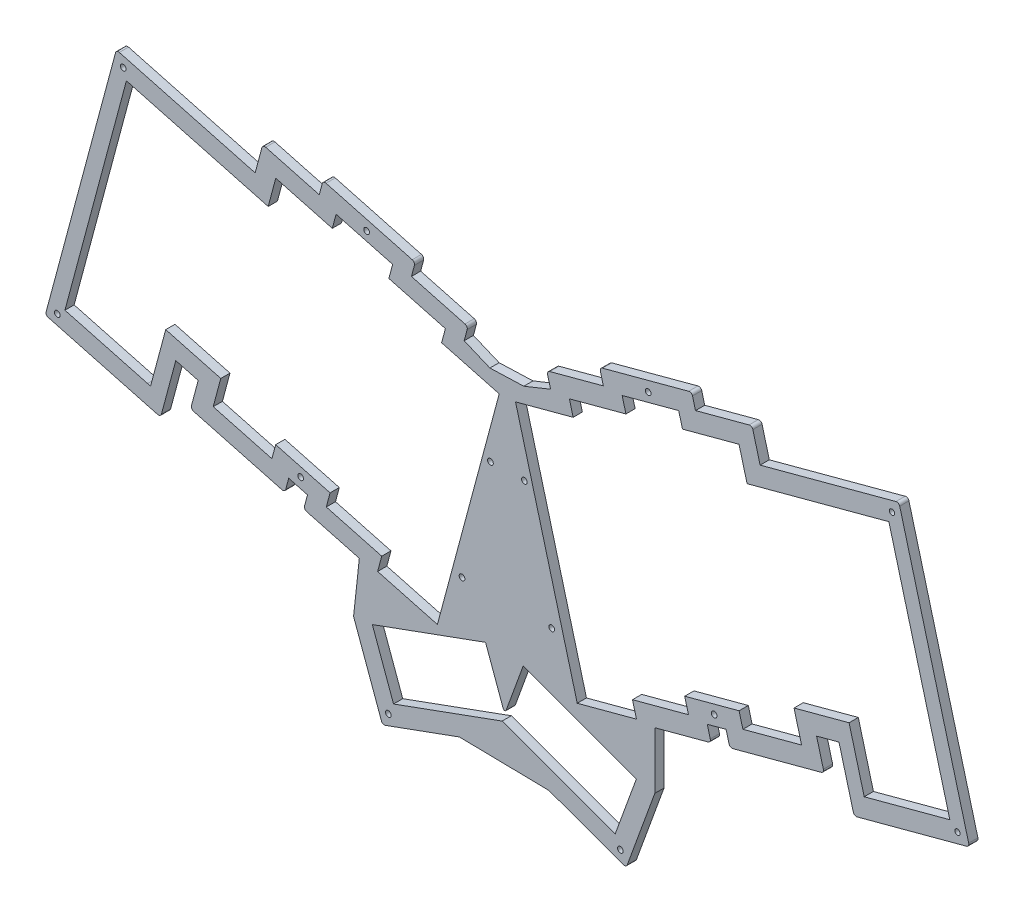
SolidWorks part; units mm, degrees
ref_plane "Front Plane" through (0, 0, 0) normal (0, 0, 1) x (1, 0, 0)
ref_plane "Top Plane" through (0, 0, 0) normal (0, 1, 0) x (1, 0, 0)
ref_plane "Right Plane" through (0, 0, 0) normal (1, 0, 0) x (0, 0, -1)
sketch "Model" plane through (0, 0, 0) normal (0, 0, 1) x (1, 0, 0)
  line L0 (282.165, 226.202) -> (288.4436, 227.8841) construction
  line L1 (267.373, 281.405) -> (273.6516, 283.0871) construction
  line L2 (195.392, 284.0785) -> (194.5766, 287.1211) construction
  line L3 (100.681, 283.685) -> (101.4961, 286.7277) construction
  line L4 (168.22, 168.742) -> (181.234, 164.006) construction
  line L5 (181.234, 164.006) -> (185.972, 177.021) construction
  line L6 (185.972, 177.021) -> (172.956, 181.758) construction
  line L7 (172.956, 181.758) -> (168.22, 168.742) construction
  line L8 (132.176, 184.752) -> (133.281, 181.717) construction
  line L9 (133.281, 181.717) -> (131.706, 181.144) construction
  line L10 (131.706, 181.144) -> (130.099, 185.56) construction
  line L11 (130.099, 185.56) -> (117.085, 180.823) construction
  line L12 (117.085, 180.823) -> (118.692, 176.407) construction
  line L13 (118.692, 176.407) -> (117.118, 175.834) construction
  line L14 (117.118, 175.834) -> (116.013, 178.869) construction
  line L15 (116.013, 178.869) -> (109.812, 176.612) construction
  line L16 (109.812, 176.612) -> (110.917, 173.576) construction
  line L17 (110.917, 173.576) -> (110.141, 173.294) construction
  line L18 (110.141, 173.294) -> (111.048, 170.804) construction
  line L19 (111.048, 170.804) -> (111.822, 171.086) construction
  line L20 (111.822, 171.086) -> (113.968, 165.194) construction
  line L21 (113.968, 165.194) -> (115.588, 165.784) construction
  line L22 (115.588, 165.784) -> (115.999, 164.656) construction
  line L23 (115.999, 164.656) -> (118.959, 165.734) construction
  line L24 (118.959, 165.734) -> (118.549, 166.861) construction
  line L25 (118.549, 166.861) -> (120.169, 167.452) construction
  line L26 (120.169, 167.452) -> (118.641, 171.651) construction
  line L27 (118.641, 171.651) -> (120.215, 172.224) construction
  line L28 (120.215, 172.224) -> (121.821, 167.809) construction
  line L29 (121.821, 167.809) -> (134.837, 172.545) construction
  line L30 (134.837, 172.545) -> (133.23, 176.962) construction
  line L31 (133.23, 176.962) -> (134.804, 177.535) construction
  line L32 (134.804, 177.535) -> (136.332, 173.335) construction
  line L33 (136.332, 173.335) -> (137.953, 173.925) construction
  line L34 (137.953, 173.925) -> (138.363, 172.796) construction
  line L35 (138.363, 172.796) -> (141.323, 173.874) construction
  line L36 (141.323, 173.874) -> (140.913, 175.001) construction
  line L37 (140.913, 175.001) -> (142.533, 175.592) construction
  line L38 (142.533, 175.592) -> (140.389, 181.483) construction
  line L39 (140.389, 181.483) -> (141.165, 181.766) construction
  line L40 (141.165, 181.766) -> (140.258, 184.256) construction
  line L41 (140.258, 184.256) -> (139.484, 183.974) construction
  line L42 (139.484, 183.974) -> (138.378, 187.009) construction
  line L43 (138.378, 187.009) -> (132.176, 184.752) construction
  line L44 (150.319, 175.258) -> (163.333, 170.521) construction
  line L45 (163.333, 170.521) -> (168.071, 183.535) construction
  line L46 (168.071, 183.535) -> (155.055, 188.273) construction
  line L47 (155.055, 188.273) -> (150.319, 175.258) construction
  line L48 (109.952, 197.835) -> (123.33, 194.251) construction
  line L49 (123.33, 194.251) -> (126.916, 207.629) construction
  line L50 (126.916, 207.629) -> (113.537, 211.213) construction
  line L51 (113.537, 211.213) -> (109.952, 197.835) construction
  line L52 (169.157, 208.022) -> (172.741, 194.644) construction
  line L53 (172.741, 194.644) -> (186.119, 198.228) construction
  line L54 (186.119, 198.228) -> (182.535, 211.607) construction
  line L55 (182.535, 211.607) -> (169.157, 208.022) construction
  line L56 (92.7848, 207.366) -> (106.163, 203.781) construction
  line L57 (106.163, 203.781) -> (109.747, 217.159) construction
  line L58 (109.747, 217.159) -> (96.369, 220.744) construction
  line L59 (96.369, 220.744) -> (92.7848, 207.366) construction
  line L60 (186.326, 217.552) -> (189.91, 204.174) construction
  line L61 (189.91, 204.174) -> (203.288, 207.759) construction
  line L62 (203.288, 207.759) -> (199.704, 221.137) construction
  line L63 (199.704, 221.137) -> (186.326, 217.552) construction
  line L64 (114.883, 216.236) -> (128.261, 212.652) construction
  line L65 (128.261, 212.652) -> (131.845, 226.03) construction
  line L66 (131.845, 226.03) -> (118.467, 229.614) construction
  line L67 (118.467, 229.614) -> (114.883, 216.236) construction
  line L68 (164.226, 226.423) -> (167.812, 213.045) construction
  line L69 (167.812, 213.045) -> (181.19, 216.629) construction
  line L70 (181.19, 216.629) -> (177.604, 230.007) construction
  line L71 (177.604, 230.007) -> (164.226, 226.423) construction
  line L72 (75.6158, 216.896) -> (88.9938, 213.312) construction
  line L73 (88.9938, 213.312) -> (92.5781, 226.69) construction
  line L74 (92.5781, 226.69) -> (79.2, 230.274) construction
  line L75 (79.2, 230.274) -> (75.6158, 216.896) construction
  line L76 (55.9827, 217.227) -> (69.3607, 213.643) construction
  line L77 (69.3607, 213.643) -> (72.9449, 227.021) construction
  line L78 (72.9449, 227.021) -> (59.5672, 230.605) construction
  line L79 (59.5672, 230.605) -> (55.9827, 217.227) construction
  line L80 (203.494, 227.083) -> (207.078, 213.705) construction
  line L81 (207.078, 213.705) -> (220.457, 217.29) construction
  line L82 (220.457, 217.29) -> (216.872, 230.668) construction
  line L83 (216.872, 230.668) -> (203.494, 227.083) construction
  line L84 (223.128, 227.414) -> (226.712, 214.036) construction
  line L85 (226.712, 214.036) -> (240.09, 217.62) construction
  line L86 (240.09, 217.62) -> (236.506, 230.998) construction
  line L87 (236.506, 230.998) -> (223.128, 227.414) construction
  line L88 (12.1157, 219.121) -> (25.4937, 215.536) construction
  line L89 (25.4937, 215.536) -> (29.078, 228.914) construction
  line L90 (29.078, 228.914) -> (15.7, 232.499) construction
  line L91 (15.7, 232.499) -> (12.1157, 219.121) construction
  line L92 (266.995, 229.307) -> (270.579, 215.929) construction
  line L93 (270.579, 215.929) -> (283.957, 219.513) construction
  line L94 (283.957, 219.513) -> (280.373, 232.891) construction
  line L95 (280.373, 232.891) -> (266.995, 229.307) construction
  line L96 (97.7138, 225.767) -> (111.092, 222.183) construction
  line L97 (111.092, 222.183) -> (114.677, 235.56) construction
  line L98 (114.677, 235.56) -> (101.299, 239.145) construction
  line L99 (101.299, 239.145) -> (97.7138, 225.767) construction
  line L100 (181.394, 235.953) -> (184.98, 222.575) construction
  line L101 (184.98, 222.575) -> (198.357, 226.159) construction
  line L102 (198.357, 226.159) -> (194.773, 239.538) construction
  line L103 (194.773, 239.538) -> (181.394, 235.953) construction
  line L104 (40.0473, 231.357) -> (53.425, 227.773) construction
  line L105 (53.425, 227.773) -> (57.0096, 241.151) construction
  line L106 (57.0096, 241.151) -> (43.6316, 244.735) construction
  line L107 (43.6316, 244.735) -> (40.0473, 231.357) construction
  line L108 (239.062, 241.545) -> (242.648, 228.166) construction
  line L109 (242.648, 228.166) -> (256.024, 231.75) construction
  line L110 (256.024, 231.75) -> (252.44, 245.128) construction
  line L111 (252.44, 245.128) -> (239.062, 241.545) construction
  line L112 (119.814, 234.637) -> (133.192, 231.053) construction
  line L113 (133.192, 231.053) -> (136.776, 244.431) construction
  line L114 (136.776, 244.431) -> (123.396, 248.015) construction
  line L115 (123.396, 248.015) -> (119.814, 234.637) construction
  line L116 (159.297, 244.824) -> (162.88, 231.445) construction
  line L117 (162.88, 231.445) -> (176.258, 235.03) construction
  line L118 (176.258, 235.03) -> (172.675, 248.408) construction
  line L119 (172.675, 248.408) -> (159.297, 244.824) construction
  line L120 (80.5462, 235.297) -> (93.9243, 231.713) construction
  line L121 (93.9243, 231.713) -> (97.5099, 245.091) construction
  line L122 (97.5099, 245.091) -> (84.1304, 248.675) construction
  line L123 (84.1304, 248.675) -> (80.5462, 235.297) construction
  line L124 (60.912, 235.628) -> (74.2901, 232.044) construction
  line L125 (74.2901, 232.044) -> (77.8757, 245.422) construction
  line L126 (77.8757, 245.422) -> (64.4977, 249.006) construction
  line L127 (64.4977, 249.006) -> (60.912, 235.628) construction
  line L128 (198.563, 245.484) -> (202.147, 232.106) construction
  line L129 (202.147, 232.106) -> (215.525, 235.692) construction
  line L130 (215.525, 235.692) -> (211.941, 249.069) construction
  line L131 (211.941, 249.069) -> (198.563, 245.484) construction
  line L132 (218.196, 245.814) -> (221.782, 232.436) construction
  line L133 (221.782, 232.436) -> (235.16, 236.021) construction
  line L134 (235.16, 236.021) -> (231.574, 249.399) construction
  line L135 (231.574, 249.399) -> (218.196, 245.814) construction
  line L136 (17.045, 237.521) -> (30.423, 233.937) construction
  line L137 (30.423, 233.937) -> (34.0086, 247.315) construction
  line L138 (34.0086, 247.315) -> (20.6306, 250.899) construction
  line L139 (20.6306, 250.899) -> (17.045, 237.521) construction
  line L140 (262.063, 247.708) -> (265.649, 234.33) construction
  line L141 (265.649, 234.33) -> (279.026, 237.914) construction
  line L142 (279.026, 237.914) -> (275.442, 251.292) construction
  line L143 (275.442, 251.292) -> (262.063, 247.708) construction
  line L144 (102.646, 244.168) -> (116.024, 240.584) construction
  line L145 (116.024, 240.584) -> (119.607, 253.962) construction
  line L146 (119.607, 253.962) -> (106.229, 257.546) construction
  line L147 (106.229, 257.546) -> (102.646, 244.168) construction
  line L148 (176.465, 254.354) -> (180.049, 240.976) construction
  line L149 (180.049, 240.976) -> (193.427, 244.56) construction
  line L150 (193.427, 244.56) -> (189.843, 257.938) construction
  line L151 (189.843, 257.938) -> (176.465, 254.354) construction
  line L152 (44.9778, 249.759) -> (58.3558, 246.174) construction
  line L153 (58.3558, 246.174) -> (61.94, 259.553) construction
  line L154 (61.94, 259.553) -> (48.562, 263.136) construction
  line L155 (48.562, 263.136) -> (44.9778, 249.759) construction
  line L156 (234.133, 259.945) -> (237.717, 246.567) construction
  line L157 (237.717, 246.567) -> (251.095, 250.151) construction
  line L158 (251.095, 250.151) -> (247.511, 263.529) construction
  line L159 (247.511, 263.529) -> (234.133, 259.945) construction
  line L160 (124.743, 253.038) -> (138.122, 249.454) construction
  line L161 (138.122, 249.454) -> (141.707, 262.832) construction
  line L162 (141.707, 262.832) -> (128.329, 266.416) construction
  line L163 (128.329, 266.416) -> (124.743, 253.038) construction
  line L164 (154.365, 263.224) -> (157.951, 249.845) construction
  line L165 (157.951, 249.845) -> (171.329, 253.432) construction
  line L166 (171.329, 253.432) -> (167.743, 266.809) construction
  line L167 (167.743, 266.809) -> (154.365, 263.224) construction
  line L168 (85.477, 253.699) -> (98.855, 250.114) construction
  line L169 (98.855, 250.114) -> (102.439, 263.492) construction
  line L170 (102.439, 263.492) -> (89.0612, 267.076) construction
  line L171 (89.0612, 267.076) -> (85.477, 253.699) construction
  line L172 (65.8442, 254.03) -> (79.2219, 250.443) construction
  line L173 (79.2219, 250.443) -> (82.8065, 263.823) construction
  line L174 (82.8065, 263.823) -> (69.427, 267.407) construction
  line L175 (69.427, 267.407) -> (65.8442, 254.03) construction
  line L176 (193.632, 263.885) -> (197.218, 250.507) construction
  line L177 (197.218, 250.507) -> (210.596, 254.092) construction
  line L178 (210.596, 254.092) -> (207.01, 267.47) construction
  line L179 (207.01, 267.47) -> (193.632, 263.885) construction
  line L180 (213.267, 264.215) -> (216.851, 250.837) construction
  line L181 (216.851, 250.837) -> (230.229, 254.422) construction
  line L182 (230.229, 254.422) -> (226.645, 267.8) construction
  line L183 (226.645, 267.8) -> (213.267, 264.215) construction
  line L184 (21.977, 255.922) -> (35.355, 252.338) construction
  line L185 (35.355, 252.338) -> (38.9378, 265.716) construction
  line L186 (38.9378, 265.716) -> (25.5598, 269.3) construction
  line L187 (25.5598, 269.3) -> (21.977, 255.922) construction
  line L188 (257.132, 266.109) -> (260.718, 252.729) construction
  line L189 (260.718, 252.729) -> (274.096, 256.315) construction
  line L190 (274.096, 256.315) -> (270.512, 269.693) construction
  line L191 (270.512, 269.693) -> (257.132, 266.109) construction
  line L192 (107.575, 262.569) -> (120.953, 258.984) construction
  line L193 (120.953, 258.984) -> (124.539, 272.362) construction
  line L194 (124.539, 272.362) -> (111.161, 275.947) construction
  line L195 (111.161, 275.947) -> (107.575, 262.569) construction
  line L196 (171.534, 272.755) -> (175.118, 259.377) construction
  line L197 (175.118, 259.377) -> (188.496, 262.961) construction
  line L198 (188.496, 262.961) -> (184.912, 276.339) construction
  line L199 (184.912, 276.339) -> (171.534, 272.755) construction
  line L200 (49.9071, 268.159) -> (63.2852, 264.575) construction
  line L201 (63.2852, 264.575) -> (66.8708, 277.953) construction
  line L202 (66.8708, 277.953) -> (53.4928, 281.537) construction
  line L203 (53.4928, 281.537) -> (49.9071, 268.159) construction
  line L204 (229.201, 278.346) -> (232.786, 264.968) construction
  line L205 (232.786, 264.968) -> (246.164, 268.554) construction
  line L206 (246.164, 268.554) -> (242.579, 281.932) construction
  line L207 (242.579, 281.932) -> (229.201, 278.346) construction
  line L208 (90.4074, 272.099) -> (103.785, 268.515) construction
  line L209 (103.785, 268.515) -> (107.37, 281.893) construction
  line L210 (107.37, 281.893) -> (93.992, 285.477) construction
  line L211 (93.992, 285.477) -> (90.4074, 272.099) construction
  line L212 (70.7732, 272.43) -> (84.1513, 268.844) construction
  line L213 (84.1513, 268.844) -> (87.7369, 282.222) construction
  line L214 (87.7369, 282.222) -> (74.3589, 285.808) construction
  line L215 (74.3589, 285.808) -> (70.7732, 272.43) construction
  line L216 (188.703, 282.286) -> (192.286, 268.908) construction
  line L217 (192.286, 268.908) -> (205.664, 272.493) construction
  line L218 (205.664, 272.493) -> (202.081, 285.871) construction
  line L219 (202.081, 285.871) -> (188.703, 282.286) construction
  line L220 (208.336, 282.616) -> (211.92, 269.238) construction
  line L221 (211.92, 269.238) -> (225.298, 272.822) construction
  line L222 (225.298, 272.822) -> (221.714, 286.2) construction
  line L223 (221.714, 286.2) -> (208.336, 282.616) construction
  line L224 (26.9062, 274.323) -> (40.284, 270.739) construction
  line L225 (40.284, 270.739) -> (43.8697, 284.117) construction
  line L226 (43.8697, 284.117) -> (30.4919, 287.701) construction
  line L227 (30.4919, 287.701) -> (26.9062, 274.323) construction
  line L228 (252.203, 284.508) -> (255.786, 271.131) construction
  line L229 (255.786, 271.131) -> (269.165, 274.716) construction
  line L230 (269.165, 274.716) -> (265.581, 288.094) construction
  line L231 (265.581, 288.094) -> (252.203, 284.508) construction
  line L232 (37.1808, 285.909) -> (37.996, 288.9517) construction
  line L233 (28.6991, 281.012) -> (22.4207, 282.6948) construction
  line L234 (18.8047, 217.3285) -> (17.9893, 214.2859) construction
  line L235 (13.9078, 225.81) -> (7.6293, 227.4922) construction
  line L236 (277.268, 217.721) -> (278.0831, 214.6783) construction
  line L237 (271.2035, 292.2232) -> (291.0512, 218.1525) construction
  line L238 (241.3027, 224.5444) -> (243.7675, 215.3441)
  line L239 (81.0479, 284.015) -> (81.8635, 287.0576) construction
  line L240 (181.234, 164.006) -> (184.194, 162.9285) construction
  line L241 (91.0631, 284.5916) -> (72.6639, 289.5236)
  line L242 (117.85, 274.1545) -> (118.6654, 277.1971) construction
  line L243 (135.018, 264.624) -> (135.8331, 267.6667) construction
  line L244 (161.054, 265.0165) -> (160.2386, 268.0591) construction
  line L245 (178.223, 274.547) -> (177.4079, 277.5897) construction
  line L246 (215.025, 284.408) -> (214.2099, 287.4507) construction
  line L247 (258.892, 286.301) -> (258.2357, 288.7493) construction
  line L248 (196.599, 205.9665) -> (197.4144, 202.9239) construction
  line L249 (92.2965, 289.1937) -> (110.6958, 284.2617)
  line L250 (213.7675, 215.4975) -> (214.5828, 212.4548) construction
  line L251 (233.401, 215.828) -> (234.2161, 212.7853) construction
  line L252 (62.6717, 215.435) -> (61.8566, 212.3923) construction
  line L253 (82.3048, 215.104) -> (81.4897, 212.0613) construction
  line L254 (99.4739, 205.5735) -> (98.6586, 202.5309) construction
  line L255 (35.8867, 229.2106) -> (54.7701, 224.1516) construction
  line L256 (60.1818, 279.745) -> (60.9969, 282.7877) construction
  line L257 (72.6639, 289.5236) -> (70.1982, 280.3232)
  line L258 (105.8147, 195.273) -> (104.0964, 179.4507) construction
  line L259 (52.3052, 214.9511) -> (54.7701, 224.1516)
  line L260 (260.1862, 229.6041) -> (265.1156, 211.2042) construction
  line L261 (203.777, 289.5866) -> (185.3762, 284.6556)
  line L262 (30.9571, 210.8115) -> (35.8867, 229.2106) construction
  line L263 (141.707, 262.832) -> (142.5224, 265.8746) construction
  line L264 (154.365, 263.224) -> (153.5495, 266.2666) construction
  line L265 (181.234, 164.006) -> (180.1565, 161.046) construction
  line L266 (92.2965, 289.1937) -> (91.0631, 284.5916)
  line L267 (169.4396, 270.5248) -> (150.6904, 265.5004)
  line L268 (110.6958, 284.2617) -> (109.4634, 279.6637)
  line L269 (127.8626, 274.7318) -> (126.6303, 270.1341)
  line L270 (127.8626, 274.7318) -> (109.4634, 279.6637)
  line L271 (260.1862, 229.6041) -> (241.3027, 224.5444) construction
  line L272 (126.6303, 270.1341) -> (145.3813, 265.1084)
  line L273 (185.3762, 284.6556) -> (186.6084, 280.0546)
  line L274 (142.3447, 270.8715) -> (153.3719, 271.2634)
  line L275 (203.777, 289.5866) -> (205.0099, 284.986)
  line L276 (168.2073, 275.1248) -> (169.4396, 270.5248)
  line L277 (205.0099, 284.986) -> (223.4098, 289.9154)
  line L278 (223.4098, 289.9154) -> (226.0333, 280.1226)
  line L279 (186.6084, 280.0546) -> (168.2073, 275.1248)
  line L280 (104.0964, 179.4507) -> (110.9864, 160.5147)
  line L281 (152.687, 181.7655) -> (183.603, 170.5135) construction
  line L282 (110.5015, 171.0598) -> (141.4185, 182.3092) construction
  line L283 (27.2858, 222.225) -> (33.5644, 220.5428) construction
  line L284 (90.3394, 209.6904) -> (72.6399, 214.4322)
  line L285 (71.4079, 209.8335) -> (72.6399, 214.4322)
  line L286 (89.1069, 205.0898) -> (90.3394, 209.6904)
  line L287 (89.1069, 205.0898) -> (107.1497, 200.256)
  line L288 (107.1497, 200.256) -> (105.8147, 195.273)
  line L289 (110.9864, 160.5147) -> (131.4289, 167.9529)
  line L290 (71.4079, 209.8335) -> (52.3052, 214.9511)
  line L291 (5.0216, 217.7602) -> (25.0282, 292.4264) construction
  line L292 (130.099, 185.56) -> (121.821, 167.809) construction
  line L293 (190.0384, 195.7708) -> (190.0096, 178.9037) construction
  line L294 (235.89, 280.139) -> (235.2337, 282.5873) construction
  line L295 (162.6744, 167.408) -> (183.1165, 159.9688)
  line L296 (131.4289, 167.9529) -> (162.6744, 167.408) construction
  line L297 (5.0216, 217.7602) -> (30.9571, 210.8115)
  line L298 (46.7361, 229.565) -> (45.921, 226.5223) construction
  line L299 (265.1156, 211.2042) -> (291.0512, 218.1525)
  line L300 (25.0282, 292.4264) -> (70.1982, 280.3232)
  line L301 (226.0333, 280.1226) -> (271.2035, 292.2232)
  line L302 (216.1359, 206.6593) -> (215.3122, 209.7329) construction
  line L303 (128.329, 170.177) -> (129.4061, 167.2169) construction
  line L304 (249.336, 229.958) -> (250.1513, 226.9153) construction
  line L305 (268.787, 222.618) -> (262.5084, 220.9359) construction
  line L306 (109.952, 197.835) -> (106.7322, 198.6976) construction
  line L307 (-2.3268, 213.5174) -> (20.7855, 299.7748)
  line L308 (186.119, 198.228) -> (189.1617, 199.0431) construction
  line L309 (206.9661, 205.4835) -> (188.7445, 200.6005)
  line L310 (188.7445, 200.6005) -> (190.0384, 195.7708)
  line L311 (20.7855, 299.7748) -> (65.9558, 287.6716)
  line L312 (68.4216, 296.8725) -> (65.9558, 287.6716)
  line L313 (86.821, 291.9405) -> (68.4216, 296.8725)
  line L314 (88.0544, 296.5426) -> (86.821, 291.9405)
  line L315 (88.0544, 296.5426) -> (118.0445, 288.5037)
  line L316 (118.0445, 288.5037) -> (116.8121, 283.9057)
  line L317 (135.2113, 278.9738) -> (116.8121, 283.9057)
  line L318 (135.2113, 278.9738) -> (133.9791, 274.3762)
  line L319 (133.9791, 274.3762) -> (142.3447, 270.8715)
  line L320 (153.3719, 271.2634) -> (162.0915, 274.7674)
  line L321 (20.7855, 299.7748) -> (25.0282, 292.4264) construction
  line L322 (160.859, 279.3678) -> (162.0915, 274.7674)
  line L323 (179.2607, 284.2977) -> (160.859, 279.3678)
  line L324 (178.0286, 288.8984) -> (179.2607, 284.2977)
  line L325 (208.0195, 296.9352) -> (178.0286, 288.8984)
  line L326 (208.0195, 296.9352) -> (209.2525, 292.3342)
  line L327 (209.2525, 292.3342) -> (227.6528, 297.2637)
  line L328 (227.6528, 297.2637) -> (230.2763, 287.4708)
  line L329 (230.2763, 287.4708) -> (275.4462, 299.5713)
  line L330 (298.3998, 213.9096) -> (294.5027, 216.1597) construction
  line L331 (275.4462, 299.5713) -> (298.3998, 213.9096)
  line L332 (260.8726, 203.856) -> (298.3998, 213.9096)
  line L333 (255.9433, 222.2556) -> (260.8726, 203.856)
  line L334 (255.9433, 222.2556) -> (248.6509, 220.3017)
  line L335 (183.1165, 159.9688) -> (190.0096, 178.9037)
  line L336 (248.6509, 220.3017) -> (251.1158, 211.1012)
  line L337 (220.4222, 202.8783) -> (251.1158, 211.1012)
  line L338 (219.1898, 207.4775) -> (220.4222, 202.8783)
  line L339 (213.082, 205.8412) -> (219.1898, 207.4775)
  line L340 (206.9661, 205.4835) -> (205.7333, 210.084)
  line L341 (223.4323, 214.8256) -> (224.6648, 210.2265)
  line L342 (205.7333, 210.084) -> (223.4323, 214.8256)
  line L343 (214.3147, 201.2411) -> (213.082, 205.8412)
  line L344 (214.3147, 201.2411) -> (196.0393, 196.3437)
  line L345 (224.6648, 210.2265) -> (243.7675, 215.3441)
  line L346 (196.0393, 196.3437) -> (196.0078, 177.8406)
  line L347 (150.6904, 265.5004) -> (170.7656, 190.6076)
  line L348 (186.7023, 152.2789) -> (196.0078, 177.8406)
  line L349 (161.566, 161.4264) -> (186.7023, 152.2789)
  line L350 (132.4358, 161.9344) -> (161.566, 161.4264)
  line L351 (107.3996, 152.8248) -> (132.4358, 161.9344)
  line L352 (97.9807, 178.7109) -> (107.3996, 152.8248)
  line L353 (99.8582, 195.9979) -> (97.9807, 178.7109)
  line L354 (141.707, 262.832) -> (154.365, 263.224) construction
  line L355 (81.7586, 200.8468) -> (99.8582, 195.9979)
  line L356 (81.7586, 200.8468) -> (82.9911, 205.4475)
  line L357 (82.9911, 205.4475) -> (76.8829, 207.0839)
  line L358 (75.6509, 202.4852) -> (76.8829, 207.0839)
  line L359 (75.6509, 202.4852) -> (44.9569, 210.7082)
  line L360 (44.9569, 210.7082) -> (47.4218, 219.9086)
  line L361 (40.1295, 221.8623) -> (47.4218, 219.9086)
  line L362 (35.1999, 203.4631) -> (40.1295, 221.8623)
  line L363 (-2.3268, 213.5174) -> (35.1999, 203.4631)
  line L364 (20.7855, 299.7748) -> (23.0356, 295.8777) construction
  line L365 (142.5224, 265.8746) -> (153.5495, 266.2666) construction
  line L366 (275.4462, 299.5713) -> (271.2035, 292.2232) construction
  line L367 (291.0512, 218.1525) -> (298.3998, 213.9096) construction
  line L368 (-2.3268, 213.5174) -> (5.0216, 217.7602) construction
  line L369 (107.3996, 152.8248) -> (110.9864, 160.5147) construction
  line L370 (183.1165, 159.9688) -> (186.7023, 152.2789) construction
  line L371 (107.3996, 152.8248) -> (109.3018, 156.903) construction
  line L372 (184.8006, 156.3573) -> (186.7023, 152.2789) construction
  line L373 (106.163, 203.781) -> (189.91, 204.174) construction
  line L374 (101.4961, 286.7277) -> (103.0495, 292.5232) construction
  line L375 (194.5766, 287.1211) -> (193.0241, 292.9168) construction
  line L376 (23.0356, 295.8777) -> (23.8591, 298.9513) construction
  line L377 (193.0241, 292.9168) -> (193.8474, 289.8432) construction
  line L378 (214.5828, 212.4548) -> (216.1359, 206.6593) construction
  line L379 (103.0495, 292.5232) -> (102.2257, 289.4497) construction
  line L380 (275.4462, 299.5713) -> (273.1961, 295.6743) construction
  line L381 (-2.3268, 213.5174) -> (1.5702, 215.7675) construction
  line L382 (81.4897, 212.0613) -> (79.937, 206.2657) construction
  line L383 (81.4897, 212.0613) -> (79.937, 206.2657) construction
  line L384 (214.5828, 212.4548) -> (216.1359, 206.6593) construction
  line L385 (145.3813, 265.1084) -> (125.265, 190.0622)
  line L386 (190.0384, 195.7708) -> (170.7656, 190.6076)
  line L387 (148.0359, 266.0706) -> (148.0365, 203.9775) construction
  line L388 (105.8147, 195.273) -> (125.265, 190.0622)
  line L389 (104.0964, 179.4507) -> (140.9309, 192.8582)
  line L390 (190.0096, 178.9037) -> (153.1726, 192.3111)
  line L391 (152.687, 181.7655) -> (149.727, 182.8428) construction
  line L392 (131.4289, 167.9529) -> (146.3042, 173.3654)
  line L393 (153.1726, 192.3111) -> (147.152, 175.767)
  line L394 (146.3042, 173.3654) -> (162.6744, 167.408)
  line L395 (141.4185, 182.3092) -> (144.3786, 183.3863) construction
  line L396 (147.152, 175.767) -> (140.9309, 192.8582)
  line L397 (110.5015, 171.0598) -> (107.5414, 169.9827) construction
  line L398 (123.592, 183.1915) -> (122.5136, 186.1545) construction
  line L399 (105.8147, 195.273) -> (183.187, 229.264) construction
  line L400 (171.073, 185.7954) -> (164.1828, 166.8591) construction
  line L401 (112.8845, 228.8715) -> (190.0384, 195.7708) construction
  line L402 (105.8147, 195.273) -> (133.2811, 207.3395) construction
  line L403 (162.4685, 207.5989) -> (190.0384, 195.7708) construction
  line L404 (136.776, 244.431) -> (159.297, 244.824) construction
  line L405 (136.776, 244.431) -> (142.5224, 244.5313) construction
  line L406 (159.297, 244.824) -> (153.5495, 244.7237) construction
  line L407 (79.937, 206.2657) -> (80.7604, 209.3393) construction
  line L408 (-2.3268, 299.7933) -> (298.3998, 299.553) construction
  line L409 (-2.3268, 153.58) -> (298.3998, 151.5101) construction
  line L410 (-2.3268, 153.58) -> (-2.3268, 299.7933) construction
  line L411 (298.3998, 151.5101) -> (298.3998, 299.553) construction
  line L412 (33.5644, 220.5428) -> (34.5303, 220.284) construction
  line L413 (30.9571, 210.8115) -> (31.9231, 210.5526)
  line L414 (31.9231, 210.5526) -> (36.8524, 228.9519)
  line L415 (5.0216, 217.7602) -> (4.0557, 218.019)
  line L416 (25.0282, 292.4264) -> (24.0623, 292.6852)
  line L417 (4.0557, 218.019) -> (24.0623, 292.6852)
  line L418 (36.8524, 228.9519) -> (54.7701, 224.1516)
  line L419 (265.1156, 211.2042) -> (264.1496, 210.9455)
  line L420 (291.0512, 218.1525) -> (292.0172, 218.4113)
  line L421 (271.2035, 292.2232) -> (272.1694, 292.482)
  line L422 (272.1694, 292.482) -> (292.0172, 218.4113)
  line L423 (264.1496, 210.9455) -> (259.2196, 229.3451)
  line L424 (241.3027, 224.5444) -> (259.2196, 229.3451)
  line L425 (164.1828, 166.8591) -> (183.1165, 159.9688) construction
  line L426 (190.0096, 178.9037) -> (171.073, 185.7954) construction
  line L427 (99.8582, 195.9979) -> (99.8582, 195.9979) construction
  line L428 (99.8582, 195.9979) -> (97.9807, 178.7109) construction
  line L429 (150.6904, 265.5004) -> (145.3813, 265.1084) construction
  line L430 (149.6841, 271.4425) -> (145.9529, 271.1669) construction
  line L431 (133.9791, 274.3762) -> (145.9529, 271.1669) construction
  line L432 (162.0915, 274.7674) -> (149.6841, 271.4425) construction
  line L433 (256.6831, 294.5449) -> (275.4462, 299.5713) construction
  line L434 (230.2763, 287.4708) -> (256.6831, 294.5449) construction
  line L435 (196.0393, 196.3437) -> (196.0393, 196.3437) construction
  line L436 (196.0393, 196.3437) -> (196.0078, 177.8406) construction
  line L437 (226.0333, 280.1226) -> (258.2357, 288.7493) construction
  line L438 (258.2357, 288.7493) -> (271.2035, 292.2232) construction
  circle A0 centre (23.0356, 295.8777) radius 0.925
  circle A1 centre (109.3018, 156.903) radius 0.925
  circle A2 centre (184.8006, 156.3573) radius 0.925
  circle A3 centre (193.8474, 289.8432) radius 0.925
  circle A4 centre (102.2257, 289.4497) radius 0.925
  circle A5 centre (273.1961, 295.6743) radius 0.875
  circle A6 centre (1.5702, 215.7675) radius 0.925
  circle A7 centre (294.5027, 216.1597) radius 0.875
  circle A8 centre (80.7604, 209.3393) radius 0.925
  circle A9 centre (215.3122, 209.7329) radius 0.925
  circle A10 centre (133.2811, 207.3395) radius 0.925
  circle A11 centre (162.4685, 207.5989) radius 0.925
  circle A12 centre (142.5224, 244.5313) radius 0.925
  circle A13 centre (153.5495, 244.7237) radius 0.925
  point P253 (61.8566, 212.3923)
  point P289 (81.8635, 287.0576)
  point P293 (194.5766, 287.1211)
  point P295 (101.4961, 286.7277)
  point P297 (81.4897, 212.0613)
  point P361 (125.96, 176.6845)
  point P362 (125.96, 176.6845)
  point P374 (214.5828, 212.4548)
  point P377 (234.2161, 212.7853)
  point P378 (177.4079, 277.5897)
  point P386 (214.2099, 287.4507)
  dimension "D5" = 6
  dimension "D4" = 1.85
  dimension "D7" = 30.011
  dimension "D8" = 30
  dimension "D9" = 1.75
  dimension "D11" = 146.2133
  dimension "D1" = 9.5249
  dimension "D2" = 6.5
  dimension "D3" = 5
  dimension "D6" = 4.5
  dimension "D10" = 4.5
  dimension "D12" = 300.7266
  dimension "D13" = 1
extrude "Boss-Extrude1" add sketch "Model" against normal blind 3
fillet "Fillet2" radius 0.5 1 edges at (147.152, 175.767, -1.5)
fillet "Fillet3" radius 1 22 edges at (20.7855, 299.7748, -1.5) (68.4216, 296.8725, -1.5) (88.0544, 296.5426, -1.5) (135.2113, 278.9738, -1.5) (160.859, 279.3678, -1.5) (178.0286, 288.8984, -1.5) (208.0195, 296.9352, -1.5) (227.6528, 297.2637, -1.5) (275.4462, 299.5713, -1.5) (298.3998, 213.9096, -1.5) (260.8726, 203.856, -1.5) (251.1158, 211.1012, -1.5) (220.4222, 202.8783, -1.5) (214.3147, 201.2411, -1.5) (186.7023, 152.2789, -1.5) (107.3996, 152.8248, -1.5) (81.7586, 200.8468, -1.5) (75.6509, 202.4852, -1.5) (44.9569, 210.7082, -1.5) (35.1999, 203.4631, -1.5) (-2.3268, 213.5174, -1.5) (118.0445, 288.5037, -1.5)
